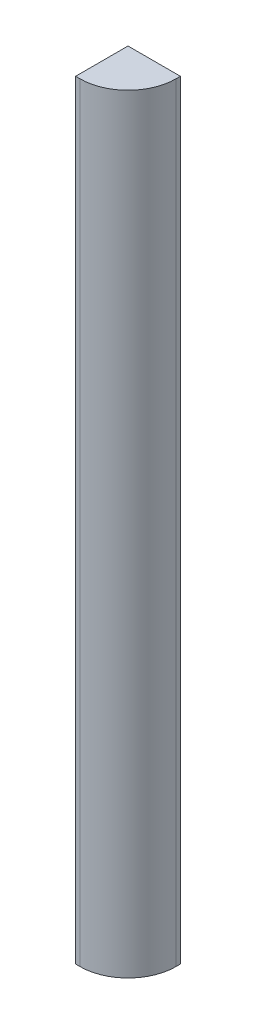
SolidWorks part; units mm, degrees
ref_plane "Front Plane" through (0, 0, 0) normal (0, 0, 1) x (1, 0, 0)
ref_plane "Top Plane" through (0, 0, 0) normal (0, 1, 0) x (1, 0, 0)
ref_plane "Right Plane" through (0, 0, 0) normal (1, 0, 0) x (0, 0, -1)
sketch "Sketch1" plane through (0, 0, 0) normal (0, 1, 0) x (1, 0, 0)
  line L1 (3, 3) -> (-3, 3)
  line L2 (3, 3) -> (3, -3)
  line L3 (3, -3) -> (-3, -3)
  line L4 (-3, 3) -> (-3, -3)
  line L5 (3, 3) -> (-3, -3) construction
  line L6 (3, -3) -> (-3, 3) construction
  point P0 (0, 0)
  dimension "D1" = 6
  dimension "D2" = 6
extrude "Boss-Extrude1" add sketch "Sketch1" along normal blind 87.99
fillet "Fillet1" radius 5.5 1 edges at (3, 43.995, 3)
